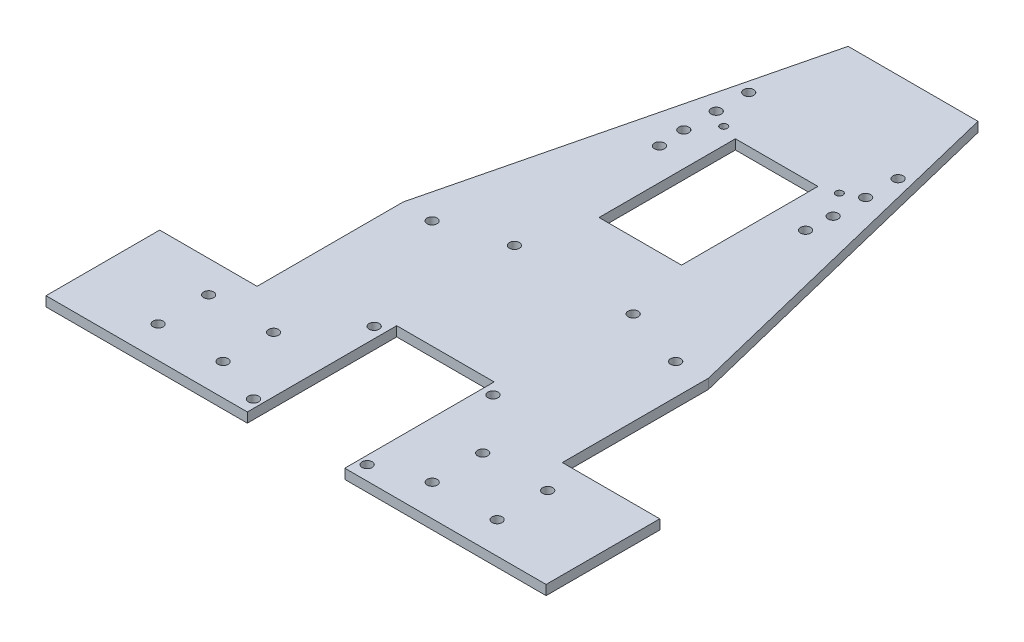
SolidWorks part; units mm, degrees
material "Acrylic (Medium-high impact)"
ref_plane "Front Plane" through (0, 0, 0) normal (0, 0, 1) x (1, 0, 0)
ref_plane "Top Plane" through (0, 0, 0) normal (0, 1, 0) x (1, 0, 0)
ref_plane "Right Plane" through (0, 0, 0) normal (1, 0, 0) x (0, 0, -1)
sketch "Sketch3" plane through (0, 0, 0) normal (0, 1, 0) x (1, 0, 0)
  line L0 (-15, -46) -> (-47, -46)
  line L1 (-47, -46) -> (-47, 34)
  line L2 (-47, 34) -> (-20, 144)
  line L3 (-20, 144) -> (20, 144)
  line L4 (20, 144) -> (47, 34)
  line L5 (47, 34) -> (47, -46)
  line L6 (47, -46) -> (15, -46)
  line L7 (15, -46) -> (15, 0)
  line L8 (15, 0) -> (-15, 0)
  line L9 (-15, 0) -> (-15, -46)
  point P11 (0, 0)
  dimension "D1" = 30
  dimension "D2" = 32
  dimension "D3" = 46
  dimension "D4" = 80
  dimension "D5" = 110
  dimension "D6" = 40
extrude "Body" add sketch "Sketch3" along normal blind 3
sketch "Sketch4" plane through (0, 3, 0) normal (0, 1, 0) x (1, 0, 0)
  line L6 (0, 0) -> (0, -41.6) construction
  line L8 (-18.29, -3.65) -> (18.29, -3.65) construction
  line L9 (-18.29, -3.65) -> (-18.29, 39.53) construction
  line L10 (-18.29, 39.53) -> (18.29, 39.53) construction
  line L11 (18.29, -3.65) -> (18.29, 39.53) construction
  circle A4 centre (-18.29, -3.65) radius 1.55
  circle A7 centre (18.29, -3.65) radius 1.55
  circle A14 centre (-18.29, 39.53) radius 1.55
  circle A15 centre (18.29, 39.53) radius 1.55
  dimension "D3" = 3.1
  dimension "D4" = 18.29
extrude "Motor Mount" cut sketch "Sketch4" against normal blind 3
sketch "Sketch5" plane through (0, 3, 0) normal (0, 1, 0) x (1, 0, 0)
  line L0 (0, 0) -> (0, 60) construction
  line L1 (-12.7, 60) -> (12.7, 60)
  line L2 (-12.7, 60) -> (-12.7, 102)
  line L3 (-12.7, 102) -> (12.7, 102)
  line L4 (12.7, 60) -> (12.7, 102)
  line L5 (-15, 0) -> (15, 0) construction
  line L6 (-17.8, 103.5) -> (17.8, 103.5) construction
  line L7 (0, 103.5) -> (0, 60) construction
  circle A0 centre (-17.8, 103.5) radius 1.1
  circle A1 centre (17.8, 103.5) radius 1.1
  dimension "D4" = 2.2
  dimension "D1" = 25.4
  dimension "D2" = 42
  dimension "D3" = 60
  dimension "D5" = 1.5
  dimension "D6" = 35.6
extrude "Protoboard Mount" cut sketch "Sketch5" against normal blind 10
sketch "Sketch8" plane through (0, 3, 0) normal (0, 1, 0) x (1, 0, 0)
  line L0 (-22.5, 88.4) -> (22.5, 88.4) construction
  line L1 (-37.5, 33.4) -> (37.5, 33.4) construction
  line L2 (-17.5, -41.6) -> (17.5, -41.6) construction
  line L3 (0, 88.4) -> (0, -41.6) construction
  line L4 (-17.5, -41.6) -> (-28, -41.6) construction
  circle A0 centre (-22.5, 88.4) radius 1.55
  circle A1 centre (22.5, 88.4) radius 1.55
  circle A2 centre (37.5, 33.4) radius 1.55
  circle A3 centre (-37.5, 33.4) radius 1.55
  circle A4 centre (-17.5, -41.6) radius 1.55
  circle A5 centre (17.5, -41.6) radius 1.55
  point P14 (0, 33.4)
  dimension "D1" = 3.1
  dimension "D2" = 45
  dimension "D3" = 75
  dimension "D4" = 35
  dimension "D5" = 75
  dimension "D6" = 55
extrude "Stand Off Mount" cut sketch "Sketch8" against normal blind 10
sketch "Sketch9" plane through (0, 3, 0) normal (0, 1, 0) x (1, 0, 0)
  line L0 (0, 0) -> (0, -46) construction
  line L1 (47, -46) -> (77, -46)
  line L2 (47, -46) -> (47, -11)
  line L3 (47, -11) -> (77, -11)
  line L4 (77, -46) -> (77, -11)
  line L5 (-15, 0) -> (15, 0) construction
  line L6 (-77, -46) -> (-77, -11)
  line L7 (-47, -11) -> (-77, -11)
  line L8 (-47, -46) -> (-47, -11)
  line L9 (-47, -46) -> (-77, -46)
  point P9 (0, 0)
  dimension "D1" = 30
  dimension "D2" = 35
extrude "Boss-Extrude1" add sketch "Sketch9" against normal up to surface (3 mm away) up to face at (22.5, 0, -89.95)
sketch "Sketch10" plane through (0, 3, 0) normal (0, 1, 0) x (1, 0, 0)
  line L0 (-77, -20.72) -> (77, -20.72) construction
  line L1 (-77, -11) -> (-77, -46) construction
  line L2 (77, -46) -> (77, -11) construction
  line L3 (-77, -36.28) -> (77, -36.28) construction
  line L4 (-77, -28.5) -> (77, -28.5) construction
  line L5 (0, 0) -> (0, -45.3992) construction
  line L6 (-15, 0) -> (15, 0) construction
  circle A0 centre (-52.2, -20.72) radius 1.55
  circle A1 centre (-32.2, -20.72) radius 1.55
  circle A2 centre (-52.2, -36.28) radius 1.55
  circle A3 centre (-32.2, -36.28) radius 1.55
  circle A8 centre (32.2, -36.28) radius 1.55
  circle A9 centre (52.2, -36.28) radius 1.55
  circle A10 centre (32.2, -20.72) radius 1.55
  circle A11 centre (52.2, -20.72) radius 1.55
  dimension "D3" = 3.1
  dimension "D1" = 15.56
  dimension "D2" = 7.78
  dimension "D4" = 24.8
  dimension "D5" = 20
extrude "Cut-Extrude1" cut sketch "Sketch10" against normal through all
sketch "Sketch11" plane through (0, 3, 0) normal (0, 1, 0) x (1, 0, 0)
  line L0 (0, 102) -> (0, 88.4) construction
  line L1 (12.7, 102) -> (-12.7, 102) construction
  line L2 (-23, 96.4) -> (-23, 106.4) construction
  line L3 (-23, 106.4) -> (-23, 116.4) construction
  line L4 (-22.5, 88.4) -> (22.5, 88.4) construction
  circle A5 centre (-23, 96.4) radius 1.55
  circle A6 centre (-23, 106.4) radius 1.55
  circle A7 centre (-23, 116.4) radius 1.55
  circle A9 centre (23, 96.4) radius 1.55
  circle A10 centre (23, 106.4) radius 1.55
  circle A11 centre (23, 116.4) radius 1.55
  point P12 (0, 88.4)
  dimension "D3" = 10
  dimension "D4" = 8
  dimension "D5" = 3.1
  dimension "D1" = 23
  dimension "D2" = 10
extrude "Caster Ball Mount" cut sketch "Sketch11" against normal through all
equation "\"D2@Sketch10\"=\"D1@Sketch10\"/2"
